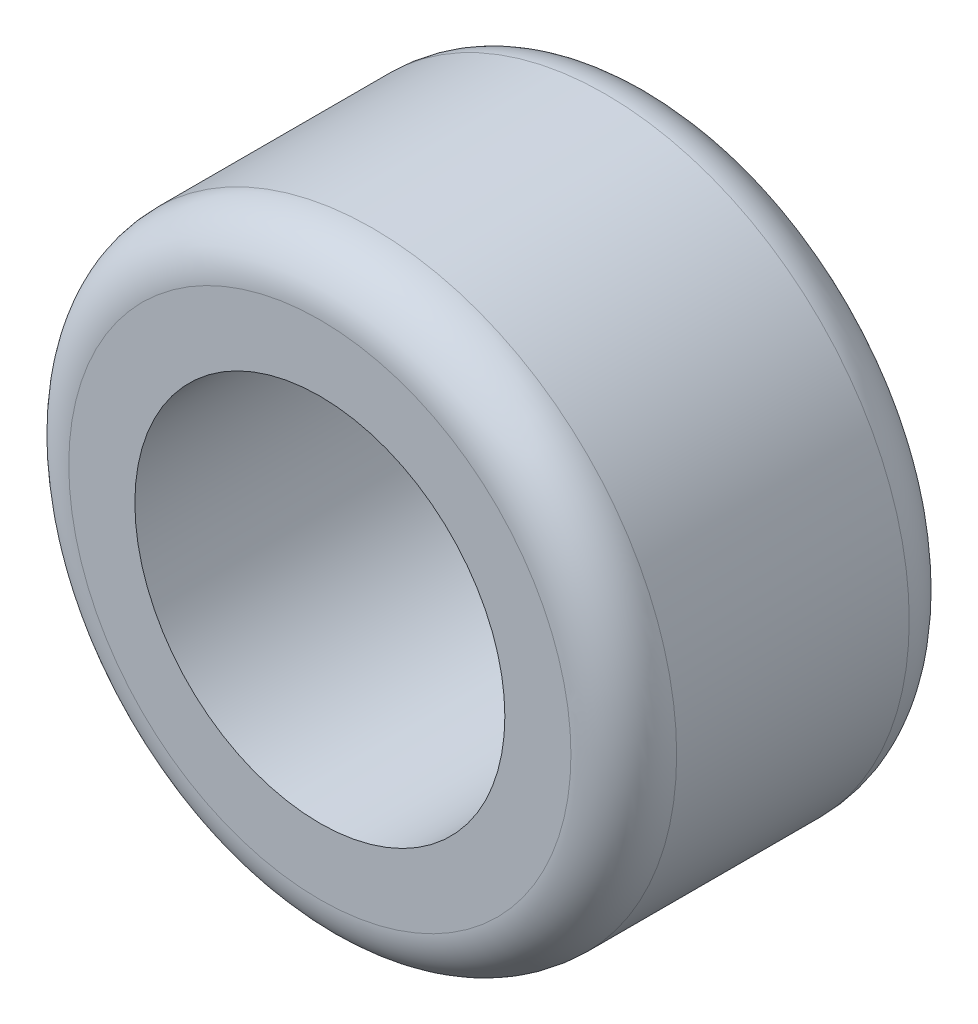
SolidWorks part; units mm, degrees
ref_plane "Front Plane" through (0, 0, 0) normal (0, 0, 1) x (1, 0, 0)
ref_plane "Top Plane" through (0, 0, 0) normal (0, 1, 0) x (1, 0, 0)
ref_plane "Right Plane" through (0, 0, 0) normal (1, 0, 0) x (0, 0, -1)
sketch "Sketch1" plane through (0, 0, 0) normal (0, 0, 1) x (1, 0, 0)
  circle A0 centre (0, 0) radius 44.45
  circle A1 centre (0, 0) radius 73.025
  dimension "D1" = 88.9
  dimension "D2" = 146.05
extrude "Boss-Extrude1" add sketch "Sketch1" along normal mid plane 81.28
fillet "Fillet1" radius 12.7 2 edges at (73.025, 0, -40.64) (73.025, 0, 40.64)
